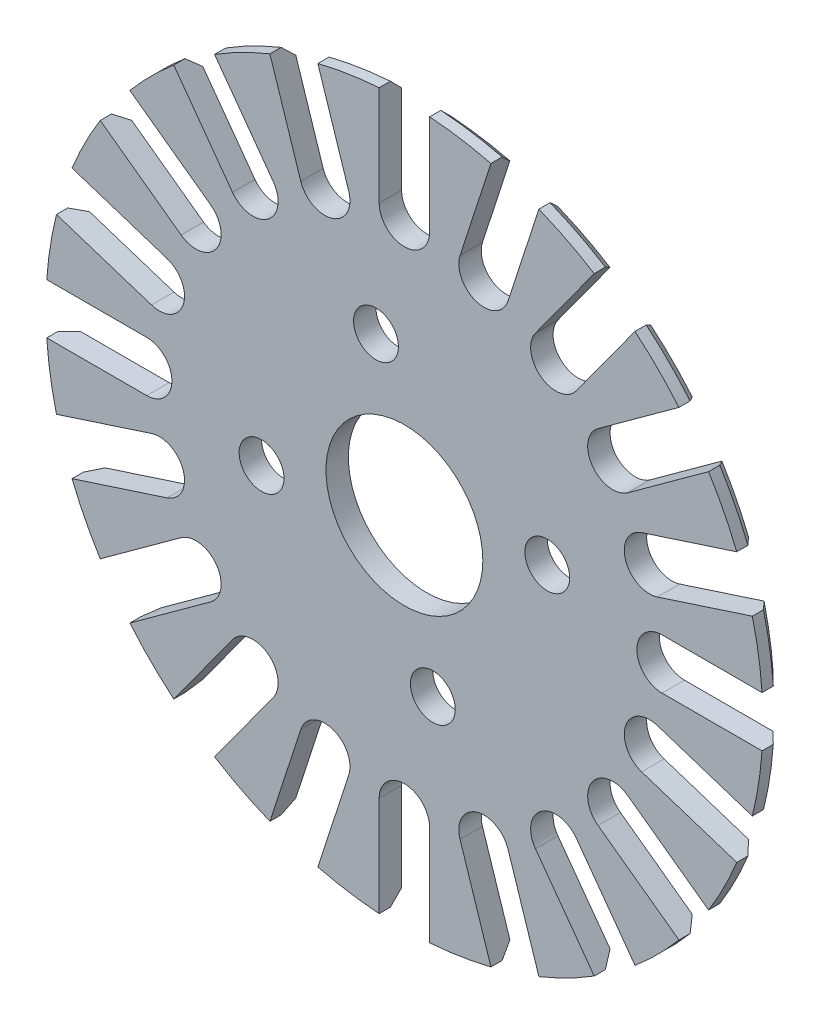
SolidWorks part; units mm, degrees
material "2A12"
ref_plane "前视基准面" through (0, 0, 0) normal (0, 0, 1) x (1, 0, 0)
ref_plane "上视基准面" through (0, 0, 0) normal (0, 1, 0) x (1, 0, 0)
ref_plane "右视基准面" through (0, 0, 0) normal (1, 0, 0) x (0, 0, -1)
sketch "草图1" plane through (0, 0, 0) normal (0, 0, 1) x (1, 0, 0)
  circle A0 centre (0, 0) radius 32
  dimension "D1" = 64
extrude "拉伸1" add sketch "草图1" along normal blind 2
sketch "草图2" plane through (0, 0, 2) normal (0, 0, 1) x (1, 0, 0)
  circle A0 centre (0, 0) radius 7
  dimension "D1" = 14
extrude "拉伸2" cut sketch "草图2" against normal blind 3
sketch "草图3" plane through (0, 0, 2) normal (0, 0, 1) x (1, 0, 0)
  line L0 (-2.5362, 12.7502) -> (0, 0) construction
  line L1 (0, 0) -> (0, 13) construction
  circle A0 centre (-2.5362, 12.7502) radius 2
  circle A1 centre (0, 0) radius 13 construction
  dimension "D1" = 26
  dimension "D2" = 4
  dimension "D3" = 11.25
extrude "拉伸3" cut sketch "草图3" against normal blind 3
pattern_circular "阵列(圆周)1" count 4 every 90 about axis through (0, 0, 0) along (0, 0, 1) of "拉伸3"
chamfer "倒角1" distance 1 angle 45 1 edges at (32, 0, 0)
sketch "草图4" plane through (0, 0, 2) normal (0, 0, 1) x (1, 0, 0)
  line L0 (-23, 2.25) -> (-31.9208, 2.25)
  line L1 (-23, -2.25) -> (-31.9208, -2.25)
  circle A0 centre (0, 0) radius 23 construction
  arc A1 (-23, -2.25) -> (-23, 2.25) centre (-23, 0) ccw
  circle A2 centre (0, 0) radius 32 construction
  arc A4 (-31.9208, 2.25) -> (-31.9208, -2.25) centre (0, 0) ccw
  dimension "D1" = 46
  dimension "D2" = 4.5
extrude "拉伸4" cut sketch "草图4" against normal blind 3
pattern_circular "阵列(圆周)3" count 20 over 360 about axis through (0, 0, 0) along (0, 0, 1) of "拉伸4"
